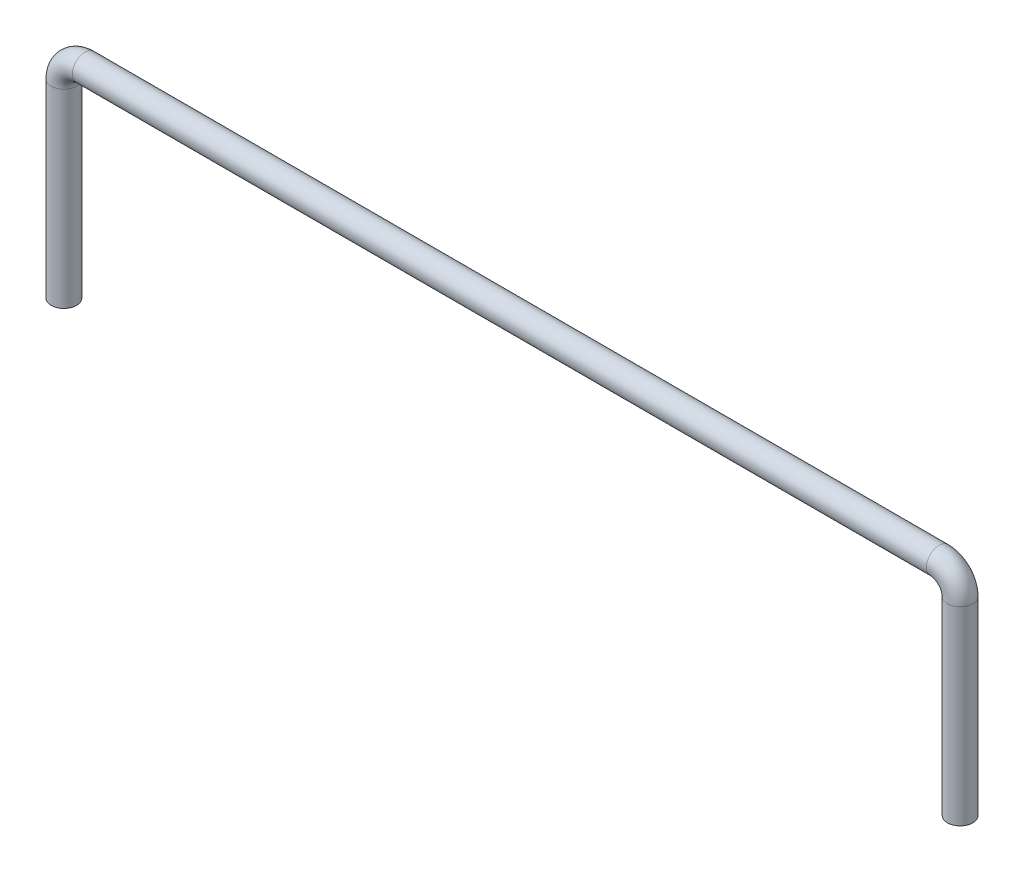
SolidWorks part; units mm, degrees
ref_plane "Front Plane" through (0, 0, 0) normal (0, 0, 1) x (1, 0, 0)
ref_plane "Top Plane" through (0, 0, 0) normal (0, 1, 0) x (1, 0, 0)
ref_plane "Right Plane" through (0, 0, 0) normal (1, 0, 0) x (0, 0, -1)
sketch "Sketch1" plane through (0, 0, 0) normal (0, 0, 1) x (1, 0, 0)
  line L0 (0, 0) -> (0, 9)
  line L1 (1, 10) -> (41.5, 10)
  line L2 (42.5, 9) -> (42.5, 0)
  arc A0 (41.5, 10) -> (42.5, 9) centre (41.5, 9) cw
  arc A1 (0, 9) -> (1, 10) centre (1, 9) cw
  point P7 (42.5, 10)
  point P10 (0, 10)
  dimension "D3" = 1
  dimension "D1" = 42.5
  dimension "D2" = 10
sweep "Sweep1" add path "Sketch1" circular profile diameter 1.2 parameters "D3"=1.2
